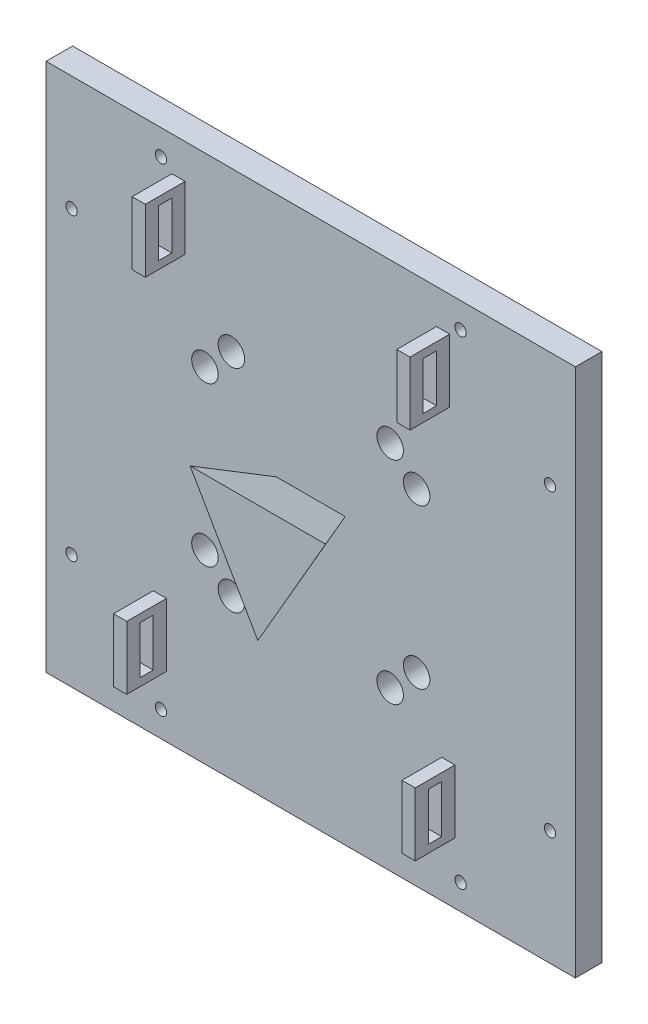
SolidWorks part; units mm, degrees
ref_plane "Front Plane" through (0, 0, 0) normal (0, 0, 1) x (1, 0, 0)
ref_plane "Top Plane" through (0, 0, 0) normal (0, 1, 0) x (1, 0, 0)
ref_plane "Right Plane" through (0, 0, 0) normal (1, 0, 0) x (0, 0, -1)
sketch "Sketch1" plane through (0, 0, 0) normal (0, 0, 1) x (1, 0, 0)
  line L1 (-100, 100) -> (100, 100)
  line L2 (-100, 100) -> (-100, -100)
  line L3 (-100, -100) -> (100, -100)
  line L4 (100, 100) -> (100, -100)
  line L5 (-100, 100) -> (100, -100) construction
  line L6 (-100, -100) -> (100, 100) construction
  point P0 (0, 0)
  dimension "D1" = 200
  dimension "D2" = 200
extrude "Boss-Extrude1" add sketch "Sketch1" along normal blind 10
sketch "Sketch2" plane through (0, 0, 10) normal (0, 0, 1) x (1, 0, 0)
  line L1 (-40, 30) -> (40, 30) construction
  line L2 (-40, 30) -> (-40, -30) construction
  line L3 (-40, -30) -> (40, -30) construction
  line L4 (40, 30) -> (40, -30) construction
  line L5 (-40, 30) -> (40, -30) construction
  line L6 (-40, -30) -> (40, 30) construction
  line L7 (30, 40) -> (-30, 40) construction
  line L8 (30, 40) -> (30, -40) construction
  line L9 (30, -40) -> (-30, -40) construction
  line L10 (-30, 40) -> (-30, -40) construction
  line L11 (30, 40) -> (-30, -40) construction
  line L12 (30, -40) -> (-30, 40) construction
  line L13 (-90.4, 56.6) -> (90.4, 56.6) construction
  line L14 (-90.4, 56.6) -> (-90.4, -56.6) construction
  line L15 (-90.4, -56.6) -> (90.4, -56.6) construction
  line L16 (90.4, 56.6) -> (90.4, -56.6) construction
  line L17 (-90.4, 56.6) -> (90.4, -56.6) construction
  line L18 (-90.4, -56.6) -> (90.4, 56.6) construction
  line L19 (-56.6, 90.4) -> (56.6, 90.4) construction
  line L20 (-56.6, 90.4) -> (-56.6, -90.4) construction
  line L21 (-56.6, -90.4) -> (56.6, -90.4) construction
  line L22 (56.6, 90.4) -> (56.6, -90.4) construction
  line L23 (-56.6, 90.4) -> (56.6, -90.4) construction
  line L24 (-56.6, -90.4) -> (56.6, 90.4) construction
  circle A0 centre (-40, 30) radius 5
  circle A1 centre (40, 30) radius 5
  circle A2 centre (40, -30) radius 5
  circle A3 centre (-40, -30) radius 5
  circle A4 centre (-30, 40) radius 5
  circle A5 centre (30, 40) radius 5
  circle A6 centre (30, -40) radius 5
  circle A7 centre (-30, -40) radius 5
  circle A8 centre (-56.6, 90.4) radius 2.15
  circle A9 centre (-90.4, 56.6) radius 2.15
  circle A10 centre (-90.4, -56.6) radius 2.15
  circle A11 centre (-56.6, -90.4) radius 2.15
  circle A12 centre (56.6, -90.4) radius 2.15
  circle A13 centre (90.4, -56.6) radius 2.15
  circle A14 centre (90.4, 56.6) radius 2.15
  circle A15 centre (56.6, 90.4) radius 2.15
  point P0 (0, 0)
  point P10 (0, 0)
  point P19 (0, 0)
  point P24 (0, 0)
  dimension "D3" = 10
  dimension "D4" = 113.2
  dimension "D6" = 4.3
  dimension "D1" = 60
  dimension "D2" = 80
  dimension "D5" = 180.8
extrude "Cut-Extrude1" cut sketch "Sketch2" against normal through all
sketch "Sketch4" plane through (0, 0, 10) normal (0, 0, 1) x (1, 0, 0)
  line L1 (0, -15) -> (12.9904, 7.5)
  line L2 (12.9904, 7.5) -> (-12.9904, 7.5)
  line L3 (-12.9904, 7.5) -> (0, -15)
  circle A0 centre (0, 0) radius 7.5 construction
  dimension "D1" = 15
extrude "Boss-Extrude2" add sketch "Sketch4" along normal blind 20
draft "Draft3" type of draft neutral plane draft angle 20 faces to draft 3 face at (0, 7.5, 20) face at (-6.4952, -3.75, 20) face at (6.4952, -3.75, 20) neutral plane through (0, 0, 10) neutral plane normal (0, 0, 1) reverse direction yes parameters "D1"=20
sketch "Sketch6" plane through (0, 0, 10) normal (0, 0, 1) x (1, 0, 0)
  line L0 (0, -100) -> (0, 100) construction
  line L1 (-100, -100) -> (100, -100) construction
  line L2 (100, 100) -> (-100, 100) construction
  line L3 (47.5, 86.9491) -> (47.5, 63.0509)
  line L4 (-52.5, 86.9491) -> (-47.5, 86.9491)
  line L5 (-52.5, 86.9491) -> (-52.5, 63.0509)
  line L6 (-52.5, 63.0509) -> (-47.5, 63.0509)
  line L7 (-47.5, 86.9491) -> (-47.5, 63.0509)
  line L8 (-52.5, 86.9491) -> (-47.5, 63.0509) construction
  line L9 (-52.5, 63.0509) -> (-47.5, 86.9491) construction
  line L10 (47.5, 63.0509) -> (52.5, 63.0509)
  line L11 (52.5, 86.9491) -> (52.5, 63.0509)
  line L12 (47.5, 86.9491) -> (52.5, 63.0509) construction
  line L13 (47.5, 63.0509) -> (52.5, 86.9491) construction
  line L14 (-59.5331, -53.0509) -> (-59.5331, -76.9491)
  line L15 (-59.5331, -76.9491) -> (-54.5331, -76.9491)
  line L16 (-54.5331, -53.0509) -> (-54.5331, -76.9491)
  line L17 (-59.5331, -53.0509) -> (-54.5331, -76.9491) construction
  line L18 (-59.5331, -76.9491) -> (-54.5331, -53.0509) construction
  line L19 (49.471, -53.0509) -> (49.471, -76.9491)
  line L20 (49.471, -76.9491) -> (54.471, -76.9491)
  line L21 (54.471, -53.0509) -> (54.471, -76.9491)
  line L22 (49.471, -53.0509) -> (54.471, -76.9491) construction
  line L23 (49.471, -76.9491) -> (54.471, -53.0509) construction
  line L24 (-59.5331, -53.0509) -> (-54.5331, -53.0509)
  line L25 (49.471, -53.0509) -> (54.471, -53.0509)
  line L26 (47.5, 86.9491) -> (52.5, 86.9491)
  point P6 (-50, 75)
  point P13 (50, 75)
  point P18 (-57.0331, -65)
  point P23 (51.971, -65)
  dimension "D1" = 5
  dimension "D2" = 23.8982
  dimension "D3" = 5
  dimension "D4" = 23.8982
  dimension "D5" = 5
  dimension "D6" = 23.8982
  dimension "D7" = 5
  dimension "D8" = 23.8982
  dimension "D9" = 50
  dimension "D10" = 100
  dimension "D11" = 140
  dimension "D12" = 140
  dimension "D13" = 25
  dimension "D14" = 25
extrude "Boss-Extrude3" add sketch "Sketch6" along normal blind 15
sketch "Sketch7" plane through (52.5, 0, 0) normal (1, 0, 0) x (0, 0, -1)
  line L0 (-25, 63.0509) -> (-25, 86.9491) construction
  line L1 (-15, 66) -> (-20, 66)
  line L2 (-15, 66) -> (-15, 84)
  line L3 (-15, 84) -> (-20, 84)
  line L4 (-20, 66) -> (-20, 84)
  line L5 (-15, 66) -> (-20, 84) construction
  line L6 (-15, 84) -> (-20, 66) construction
  line L7 (-25, 63.0509) -> (-10, 63.0509) construction
  line L8 (-15, -74) -> (-20, -74)
  line L9 (-15, -74) -> (-15, -56)
  line L10 (-15, -56) -> (-20, -56)
  line L11 (-20, -74) -> (-20, -56)
  line L12 (-15, -74) -> (-20, -56) construction
  line L13 (-15, -56) -> (-20, -74) construction
  line L16 (-25, -76.9491) -> (-10, -76.9491) construction
  line L17 (-10, -76.9491) -> (-10, -53.0509) construction
  point P0 (-17.5, 75)
  point P7 (-25, 75)
  point P8 (0, 0)
  point P10 (0, 0)
  point P12 (-17.5, 63.0509)
  point P13 (-17.5, -65)
  point P18 (0, 0)
  point P21 (-17.5, -76.9491)
  point P24 (-10, -65)
  point P25 (-20.6353, -56.3183)
  dimension "D1" = 5
  dimension "D2" = 18
  dimension "D3" = 5
  dimension "D4" = 18
extrude "Cut-Extrude3" cut sketch "Sketch7" against normal through all both and the other way through all
